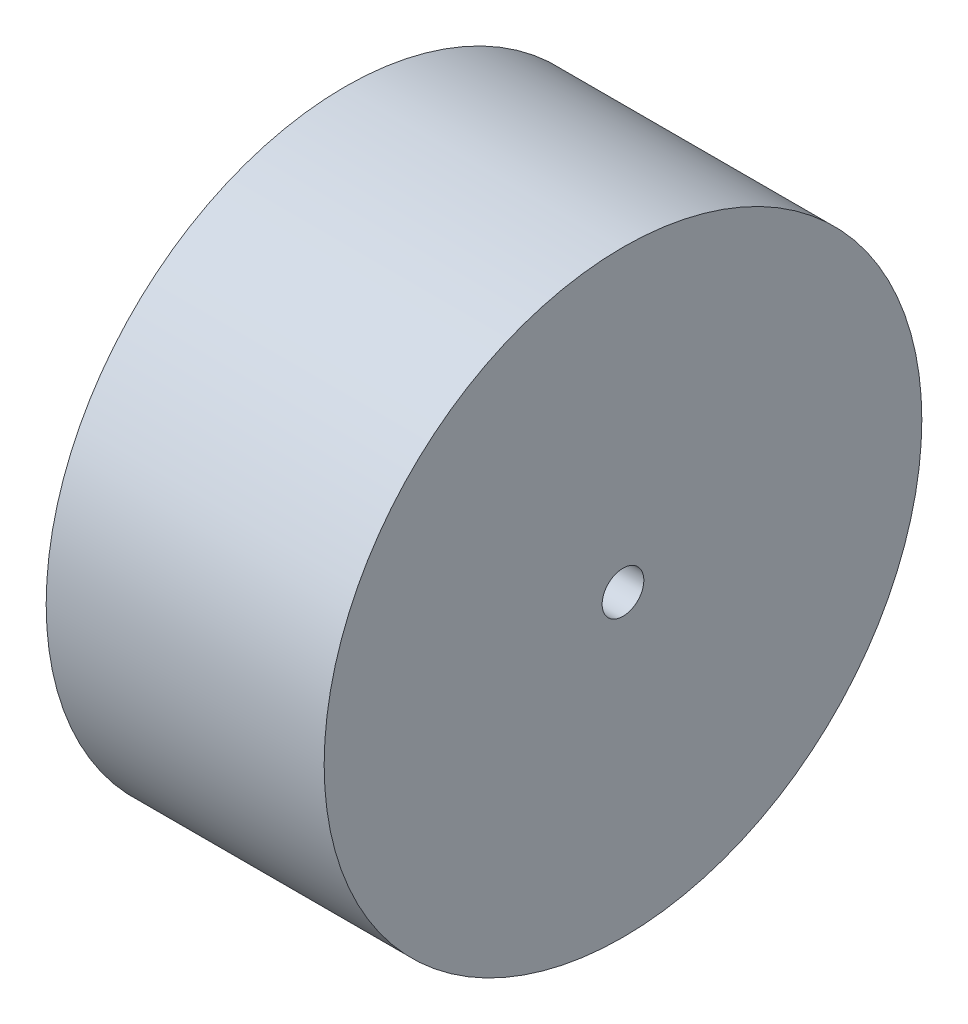
SolidWorks part; units mm, degrees
ref_plane "Alzado" through (0, 0, 0) normal (0, 0, 1) x (1, 0, 0)
ref_plane "Planta" through (0, 0, 0) normal (0, 1, 0) x (1, 0, 0)
ref_plane "Vista lateral" through (0, 0, 0) normal (1, 0, 0) x (0, 0, -1)
sketch "Croquis1" plane through (0, 0, 0) normal (1, 0, 0) x (0, 0, -1)
  circle A0 centre (0, 0) radius 21.5
  dimension "D1" = 43
extrude "Saliente-Extruir1" add sketch "Croquis1" along normal blind 20
sketch "Croquis2" plane through (20, 0, 0) normal (1, 0, 0) x (0, 0, -1)
  circle A0 centre (0, 0) radius 1.5
  dimension "D1" = 3
extrude "Cortar-Extruir1" cut sketch "Croquis2" against normal blind 30
